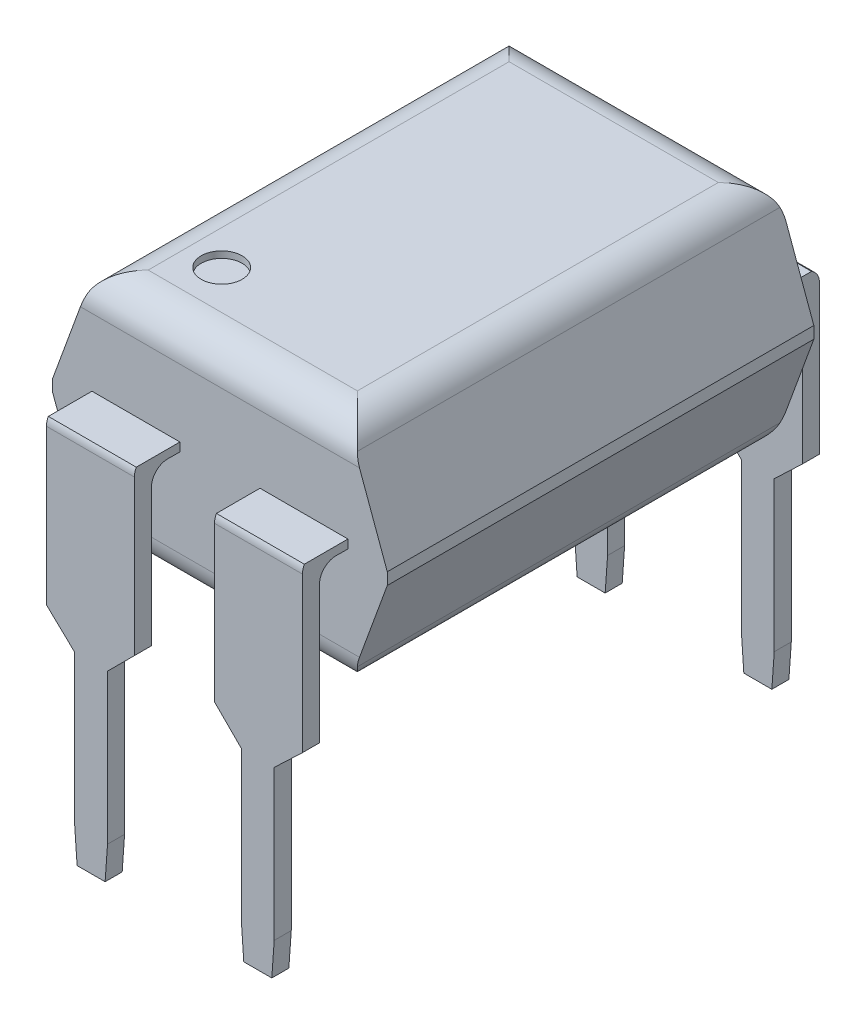
SolidWorks part; units mm, degrees
ref_plane "Front Plane" through (0, 0, 0) normal (0, 0, 1) x (1, 0, 0)
ref_plane "Top Plane" through (0, 0, 0) normal (0, 1, 0) x (1, 0, 0)
ref_plane "Right Plane" through (0, 0, 0) normal (1, 0, 0) x (0, 0, -1)
sketch "Sketch1" plane through (0, 0, 0) normal (0, 1, 0) x (1, 0, 0)
  line L1 (-2.55, -3.25) -> (2.55, -3.25)
  line L2 (-2.55, -3.25) -> (-2.55, 3.25)
  line L3 (-2.55, 3.25) -> (2.55, 3.25)
  line L4 (2.55, -3.25) -> (2.55, 3.25)
  line L5 (-2.55, -3.25) -> (2.55, 3.25) construction
  line L6 (-2.55, 3.25) -> (2.55, -3.25) construction
  point P0 (0, 0)
  dimension "D1" = 6.5
  dimension "D2" = 5.1
extrude "Boss-Extrude1" add sketch "Sketch1" along normal blind 3.5
sketch "Sketch2" plane through (0, 3.5, 0) normal (0, 1, 0) x (1, 0, 0)
  circle A0 centre (-1.0676, -2.1564) radius 0.3118
extrude "Cut-Extrude1" cut sketch "Sketch2" against normal blind 0.1
sketch "Sketch3" plane through (0, 0, 3.25) normal (0, 0, 1) x (1, 0, 0)
  line L0 (-2.55, 1.8406) -> (-1.9439, 3.5)
  line L1 (-2.55, 3.5) -> (-2.55, 0) construction
  line L2 (-2.55, 3.5) -> (2.55, 3.5) construction
  line L3 (0, 0) -> (0, 3.5) construction
  line L4 (-2.55, 1.75) -> (2.55, 1.75) construction
  line L5 (2.55, 3.5) -> (2.55, 0) construction
  line L6 (-2.55, 1.6594) -> (-1.9439, 0)
  line L7 (2.55, 1.6594) -> (1.9439, 0)
  line L8 (2.55, 1.8406) -> (1.9439, 3.5)
  line L9 (-1.9439, 3.5) -> (1.9439, 3.5)
  line L10 (1.9439, 0) -> (-1.9439, 0)
  line L11 (2.55, 1.6594) -> (2.55, 1.8406)
  line L12 (-2.55, 1.8406) -> (-2.55, 1.6594)
extrude "Cut-Extrude3" cut sketch "Sketch3" against normal through all flip side to cut
fillet "Fillet1" radius 0.5 8 edges at (1.9439, 0, 0) (-1.9439, 0, 0) (1.9439, 3.5, 0) (-1.9439, 3.5, 0) (0, 0, -3.25) (0, 3.5, -3.25) (0, 0, 3.25) (0, 3.5, 3.25)
sketch "Sketch4" plane through (-2.55, 0, 0) normal (-1, 0, 0) x (0, 0, 1)
  line L0 (-3.9366, -3.7072) -> (-3.6766, -3.7072)
  line L2 (-3.25, 1.8406) -> (3.25, 1.8406) construction
  line L3 (3.6834, -3.7072) -> (3.9434, -3.7072)
  line L4 (0, 3.5) -> (0, -1.2461) construction
  line L5 (-2.75, 3.5) -> (2.75, 3.5) construction
  line L7 (3.9434, 1.8571) -> (3.9434, -3.7072)
  line L8 (3.69, 2.107) -> (-3.69, 2.0079)
  line L9 (-3.9366, 1.758) -> (-3.9366, -3.7072)
  line L10 (3.6834, 1.5935) -> (3.6834, -3.7072)
  line L11 (3.43, 1.8435) -> (-3.43, 1.7514)
  line L12 (-3.6766, 1.5014) -> (-3.6766, -3.7072)
  arc A0 (3.6834, 1.5935) -> (3.43, 1.8435) centre (3.4334, 1.5935) ccw
  arc A1 (3.9434, 1.8571) -> (3.69, 2.107) centre (3.6934, 1.8571) ccw
  arc A2 (-3.69, 2.0079) -> (-3.9366, 1.758) centre (-3.6866, 1.758) ccw
  arc A3 (-3.43, 1.7514) -> (-3.6766, 1.5014) centre (-3.4266, 1.5014) ccw
  point P5 (0, 1.8406)
  point P6 (0, 1.8406)
  point P25 (0, 1.7975)
  point P26 (0, 2.0575)
  point P27 (-3.8066, -3.7072)
  point P28 (3.8134, -3.7072)
  point P29 (-3.6124, 1.8406)
  dimension "D1" = 0.25
  dimension "D2" = 0.26
  dimension "D3" = 7.62
  dimension "D4" = 0.26
extrude "Boss-Extrude2" add sketch "Sketch4" against normal through all separate body
sketch "Sketch5" plane through (0, 0, -3.9366) normal (0, 0, -1) x (-1, 0, 0)
  line L0 (0, 1.758) -> (0, -4.1057) construction
  line L1 (-2.55, 1.758) -> (2.55, 1.758) construction
  line L2 (-1.27, -3.7072) -> (-1.27, -0.9094) construction
  line L3 (-2.55, -3.7072) -> (2.55, -3.7072) construction
  line L4 (-1.02, -3.1928) -> (-1.02, -0.9094)
  line L5 (1.52, -0.9094) -> (1.9505, -0.5)
  line L7 (-1.02, -0.9094) -> (-0.6105, -0.5)
  line L8 (-1.52, -3.1928) -> (-1.52, -0.9094)
  line L9 (-1.52, -0.9094) -> (-1.9505, -0.5)
  line L10 (-1.9505, -0.5) -> (-1.9505, 1.758)
  line L11 (-0.6105, -0.5) -> (-0.6105, 1.758)
  line L12 (-1.9505, 1.9731) -> (-1.9505, 1.758)
  line L13 (-0.6105, 1.758) -> (-0.6105, 1.9731)
  line L14 (-0.6105, 1.9731) -> (-1.9505, 1.9731)
  line L15 (-1.0565, -3.7072) -> (-1.02, -3.1928)
  line L16 (-1.4835, -3.7072) -> (-1.52, -3.1928)
  line L17 (-1.4835, -3.7072) -> (-1.0565, -3.7072)
  line L18 (1.52, -3.1928) -> (1.52, -0.9094)
  line L19 (1.4835, -3.7072) -> (1.52, -3.1928)
  line L20 (1.4835, -3.7072) -> (1.0565, -3.7072)
  line L21 (1.0565, -3.7072) -> (1.02, -3.1928)
  line L22 (1.02, -0.9094) -> (0.6105, -0.5)
  line L23 (1.02, -3.1928) -> (1.02, -0.9094)
  line L24 (0.6105, 1.758) -> (0.6105, 1.9731)
  line L25 (0.6105, -0.5) -> (0.6105, 1.758)
  line L26 (0.6105, 1.9731) -> (1.9505, 1.9731)
  line L27 (1.9505, 1.9731) -> (1.9505, 1.758)
  line L28 (1.9505, -0.5) -> (1.9505, 1.758)
  point P16 (0, -0.5)
  dimension "D1" = 1.27
  dimension "D2" = 0.5
  dimension "D3" = 1.34
extrude "Cut-Extrude7" cut sketch "Sketch5" against normal through all both and the other way through all flip side to cut
